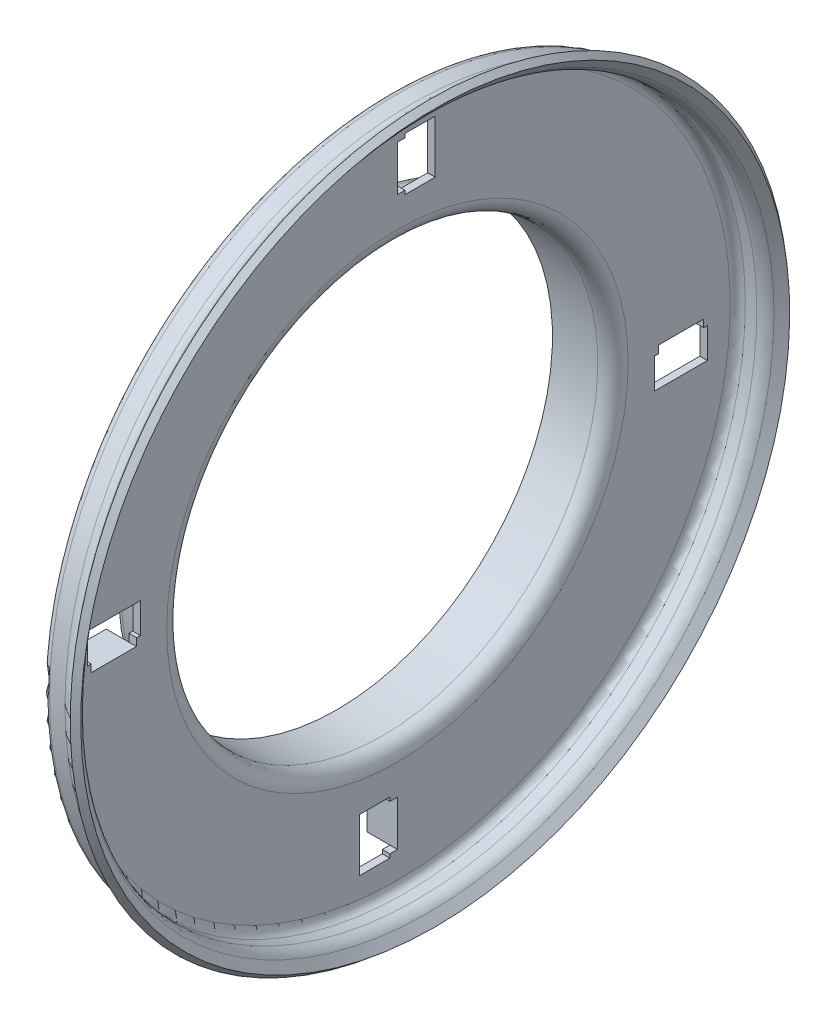
SolidWorks part; units mm, degrees
material "铸造合金钢"
ref_plane "前视基准面" through (0, 0, 0) normal (0, 0, 1) x (1, 0, 0)
ref_plane "上视基准面" through (0, 0, 0) normal (0, 1, 0) x (1, 0, 0)
ref_plane "右视基准面" through (0, 0, 0) normal (1, 0, 0) x (0, 0, -1)
sketch "草图1" plane through (0, 0, 0) normal (0, 0, 1) x (1, 0, 0)
  line L0 (-28.0837, 0) -> (47.5488, 0) construction
  line L1 (-38.0837, -28.5) -> (-32.0837, -28.5)
  line L2 (-30.0837, -30.5) -> (-30.0837, -44)
  line L3 (-29.0837, -45) -> (-27.5655, -45)
  line L4 (-26.0242, -45.7255) -> (-25.0837, -46.8627)
  line L5 (-25.0837, -46.8627) -> (-25.8544, -47.5)
  line L6 (-25.8544, -47.5) -> (-26.4949, -46.7255)
  line L7 (-28.0362, -46) -> (-30.0837, -46)
  line L8 (-31.0837, -45) -> (-31.0837, -31.5)
  line L9 (-33.0837, -29.5) -> (-37.0837, -29.5)
  arc A0 (-38.0837, -28.5) -> (-37.0837, -29.5) centre (-37.0837, -28.5) ccw
  arc A1 (-28.0362, -46) -> (-26.4949, -46.7255) centre (-28.0362, -48) cw
  arc A2 (-27.5655, -45) -> (-26.0242, -45.7255) centre (-27.5655, -47) cw
  arc A3 (-29.0837, -45) -> (-30.0837, -44) centre (-29.0837, -44) cw
  arc A4 (-31.0837, -45) -> (-30.0837, -46) centre (-30.0837, -45) ccw
  arc A5 (-31.0837, -31.5) -> (-33.0837, -29.5) centre (-33.0837, -31.5) ccw
  arc A6 (-30.0837, -30.5) -> (-32.0837, -28.5) centre (-32.0837, -30.5) ccw
  point P20 (-30.0837, -45)
  point P25 (-31.0837, -29.5)
  point P28 (-30.0837, -28.5)
  dimension "D2" = 1
  dimension "D8" = 2
  dimension "D9" = 2
  dimension "D11" = 1
  dimension "D12" = 1
  dimension "D14" = 1
  dimension "D15" = 2
  dimension "D1" = 28.5
  dimension "D4" = 1
  dimension "D6" = 1
  dimension "D7" = 1
  dimension "D10" = 47.5
  dimension "D13" = 10
  dimension "D16" = 6
revolve "旋转1" add sketch "草图1" angle 360 about L0
sketch "草图3" plane through (-30.0837, 0, 0) normal (1, 0, 0) x (0, 0, -1)
  line L0 (0, 39.4073) -> (0, -40.2099) construction
  line L1 (-39.9691, 0) -> (39.8086, 0) construction
  line L2 (0, -34.5) -> (-1, -34.4855)
  line L3 (-1, -34.4855) -> (-1, -33.9855)
  line L4 (-1, -33.9855) -> (-5, -33.9855)
  line L5 (-5, -33.9855) -> (-5, -40.9855)
  line L6 (-5, -40.9855) -> (-1, -40.9855)
  line L7 (-1, -40.9855) -> (-1, -40.4855)
  line L8 (-1, -40.4855) -> (0, -40.4855)
  line L9 (0, -40.4855) -> (0, -34.5)
  line L10 (-33.9855, 1) -> (-33.9855, 5)
  line L11 (-34.4855, 1) -> (-33.9855, 1)
  line L12 (-34.5, 0) -> (-34.4855, 1)
  line L13 (-40.4855, 0) -> (-34.5, 0)
  line L14 (-40.4855, 1) -> (-40.4855, 0)
  line L15 (-40.9855, 1) -> (-40.4855, 1)
  line L16 (-40.9855, 5) -> (-40.9855, 1)
  line L17 (-33.9855, 5) -> (-40.9855, 5)
  line L18 (1, 33.9855) -> (5, 33.9855)
  line L19 (1, 34.4855) -> (1, 33.9855)
  line L20 (0, 34.5) -> (1, 34.4855)
  line L21 (0, 40.4855) -> (0, 34.5)
  line L22 (1, 40.4855) -> (0, 40.4855)
  line L23 (1, 40.9855) -> (1, 40.4855)
  line L24 (5, 40.9855) -> (1, 40.9855)
  line L25 (5, 33.9855) -> (5, 40.9855)
  line L26 (33.9855, -1) -> (33.9855, -5)
  line L27 (34.4855, -1) -> (33.9855, -1)
  line L28 (34.5, 0) -> (34.4855, -1)
  line L29 (40.4855, 0) -> (34.5, 0)
  line L30 (40.4855, -1) -> (40.4855, 0)
  line L31 (40.9855, -1) -> (40.4855, -1)
  line L32 (40.9855, -5) -> (40.9855, -1)
  line L33 (33.9855, -5) -> (40.9855, -5)
  point P40 (0, 0)
  dimension "D1" = 4
  dimension "D2" = 4
  dimension "D3" = 7
  dimension "D4" = 5
  dimension "D5" = 4
  dimension "D6" = 0.5
  dimension "D7" = 0.5
extrude "切除-拉伸1" cut sketch "草图3" against normal through all
sketch "草图4" plane through (-31.0837, 0, 0) normal (-1, 0, 0) x (0, 0, 1)
  line L0 (0, 40.4855) -> (1, 40.4855)
  line L1 (1, 40.4855) -> (1, 34.4855)
  line L2 (1, 34.4855) -> (0, 34.5)
  line L3 (0, 40.4855) -> (0, 34.5)
  line L4 (34.4855, -1) -> (34.5, 0)
  line L5 (40.4855, -1) -> (34.4855, -1)
  line L6 (40.4855, 0) -> (40.4855, -1)
  line L7 (40.4855, 0) -> (34.5, 0)
  line L8 (-1, -34.4855) -> (0, -34.5)
  line L9 (-1, -40.4855) -> (-1, -34.4855)
  line L10 (0, -40.4855) -> (-1, -40.4855)
  line L11 (0, -40.4855) -> (0, -34.5)
  line L12 (-34.4855, 1) -> (-34.5, 0)
  line L13 (-40.4855, 1) -> (-34.4855, 1)
  line L14 (-40.4855, 0) -> (-40.4855, 1)
  line L15 (-40.4855, 0) -> (-34.5, 0)
  point P21 (0, 0)
  dimension "D1" = 1
  dimension "D2" = 6
  dimension "D3" = 1
  dimension "D4" = 4
extrude "凸台-拉伸1" add sketch "草图4" along normal blind 3
